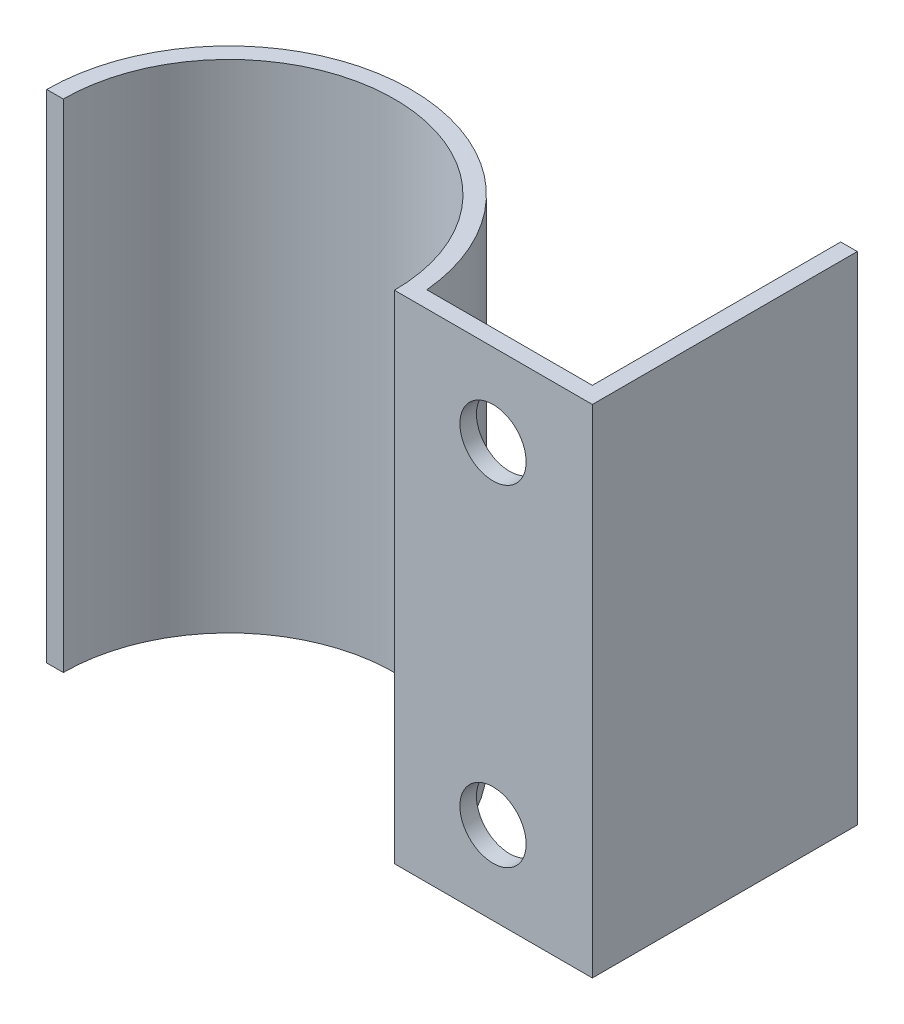
SolidWorks part; units mm, degrees
ref_plane "Alzado" through (0, 0, 0) normal (0, 0, 1) x (1, 0, 0)
ref_plane "Planta" through (0, 0, 0) normal (0, 1, 0) x (1, 0, 0)
ref_plane "Vista lateral" through (0, 0, 0) normal (1, 0, 0) x (0, 0, -1)
sketch "Sketch1" plane through (0, 0, 0) normal (0, 1, 0) x (1, 0, 0)
  line L0 (10, 0) -> (20.9545, 0)
  line L2 (20.9545, 1) -> (10.9545, 1)
  line L3 (-10, 0) -> (-11, 0)
  line L4 (20.9545, 1) -> (20.9545, 16)
  line L5 (20.9545, 16) -> (21.9545, 16)
  line L6 (21.9545, 16) -> (21.9545, 0)
  line L7 (21.9545, 0) -> (20.9545, 0)
  arc A0 (10, 0) -> (-10, 0) centre (0, 0) ccw
  arc A2 (-11, 0) -> (10.9545, 1) centre (0, 0) cw
  dimension "D1" = 10
  dimension "D3" = 11
  dimension "D2" = 1
  dimension "D4" = 10
  dimension "D5" = 15
  dimension "D6" = 1
extrude "Boss-Extrude1" add sketch "Sketch1" along normal blind 30
sketch "Sketch2" plane through (0, 0, -1) normal (0, 0, -1) x (-1, 0, 0)
  line L0 (-10.9545, 30) -> (-15.9545, 30) construction
  line L1 (-20.9545, 30) -> (-10.9545, 30) construction
  line L2 (-15.9545, 30) -> (-15.9545, 25) construction
  line L3 (-15.9545, 25) -> (-15.9545, 5) construction
  circle A0 centre (-15.9545, 25) radius 2
  circle A1 centre (-15.9545, 5) radius 2
  dimension "D1" = 5
  dimension "D2" = 20
  dimension "D3" = 5
extrude "Cut-Extrude1" cut sketch "Sketch2" against normal blind 30 contours A0 | A1
